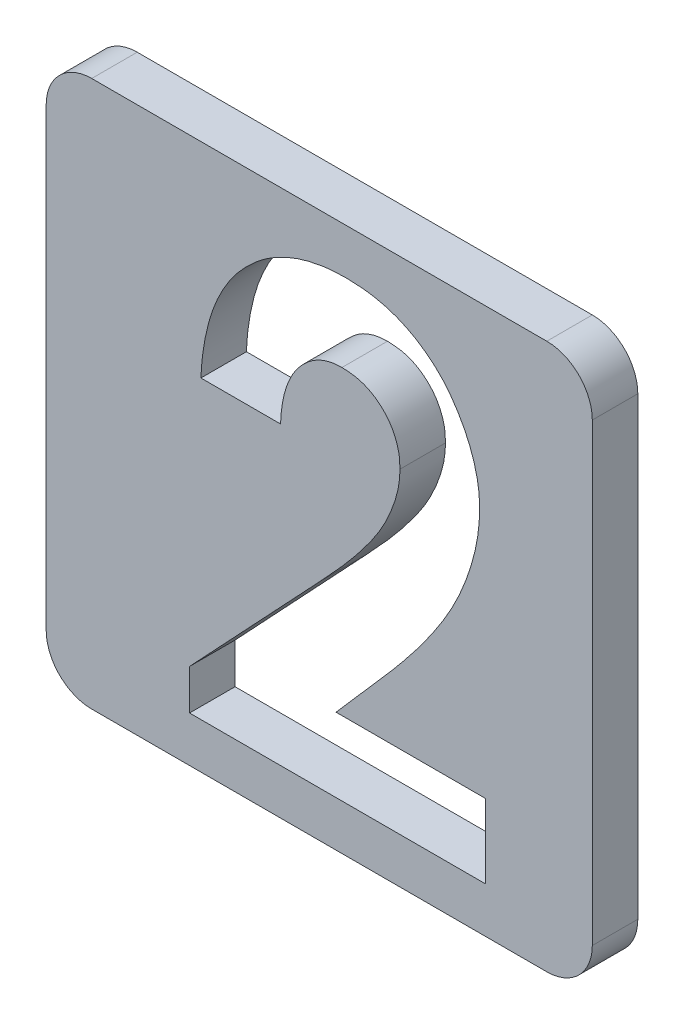
SolidWorks part; units mm, degrees
ref_plane "Front Plane" through (0, 0, 0) normal (0, 0, 1) x (1, 0, 0)
ref_plane "Top Plane" through (0, 0, 0) normal (0, 1, 0) x (1, 0, 0)
ref_plane "Right Plane" through (0, 0, 0) normal (1, 0, 0) x (0, 0, -1)
sketch "Sketch1" plane through (0, 0, 0) normal (0, 0, 1) x (1, 0, 0)
  line L1 (-50, 60) -> (50, 60)
  line L2 (-60, 50) -> (-60, -50)
  line L3 (-50, -60) -> (50, -60)
  line L4 (60, 50) -> (60, -50)
  line L5 (-60, 60) -> (60, -60) construction
  line L6 (-60, -60) -> (60, 60) construction
  arc A0 (-60, -50) -> (-50, -60) centre (-50, -50) ccw
  arc A1 (50, -60) -> (60, -50) centre (50, -50) ccw
  arc A2 (50, 60) -> (60, 50) centre (50, 50) cw
  arc A3 (-50, 60) -> (-60, 50) centre (-50, 50) ccw
  point P0 (0, 0)
  dimension "D3" = 10
  dimension "D1" = 120
  dimension "D2" = 120
extrude "Boss-Extrude1" add sketch "Sketch1" along normal blind 10 contours A3 L2 A0 L3 A1 L4 A2 L1
sketch "Sketch2" plane through (0, 0, 10) normal (0, 0, 1) x (1, 0, 0)
  line L0 (0, 0) -> (0, 40) construction
  line L1 (-50, 50) -> (50, 50) construction
  line L2 (-50, 50) -> (-50, -50) construction
  line L3 (-50, -50) -> (50, -50) construction
  line L4 (50, 50) -> (50, -50) construction
  line L5 (-50, 50) -> (50, -50) construction
  line L6 (-50, -50) -> (50, 50) construction
  line L7 (0, 40) -> (-40, 40) construction
  line L8 (-40, 40) -> (-40, 0) construction
  line L9 (-40, 0) -> (0, 0) construction
  line L11 (0, 20) -> (-20, 20) construction
  line L12 (-20, 40) -> (-20, 20) construction
  circle A0 centre (0, 40) radius 4 construction
  circle A1 centre (0, 20) radius 4 construction
  circle A2 centre (0, 0) radius 4 construction
  circle A3 centre (-20, 20) radius 4 construction
  circle A4 centre (-20, 40) radius 4 construction
  circle A5 centre (-40, 40) radius 4 construction
  circle A6 centre (0, 0) radius 4 construction
  circle A7 centre (20, 0) radius 4 construction
  circle A8 centre (40, 0) radius 4 construction
  circle A9 centre (40, 20) radius 4 construction
  circle A10 centre (40, 40) radius 4 construction
  circle A11 centre (20, 20) radius 4 construction
  circle A12 centre (0, 0) radius 4 construction
  circle A13 centre (0, -20) radius 4 construction
  circle A14 centre (0, -40) radius 4 construction
  circle A15 centre (20, -40) radius 4 construction
  circle A16 centre (40, -40) radius 4 construction
  circle A17 centre (20, -20) radius 4 construction
  circle A18 centre (0, 0) radius 4 construction
  circle A19 centre (-20, 0) radius 4 construction
  circle A20 centre (-40, 0) radius 4 construction
  circle A21 centre (-40, -20) radius 4 construction
  circle A22 centre (-40, -40) radius 4 construction
  circle A23 centre (-20, -20) radius 4 construction
  text T0 "2" font "Century Gothic" height 97.5
  point P0 (0, 0)
  point P55 (0, 0)
  dimension "D4" = 8
  dimension "D1" = 100
  dimension "D2" = 100
  dimension "D3" = 40
  dimension "D5" = 4
extrude "Cut-Extrude3" cut sketch "Sketch2" against normal blind 10
